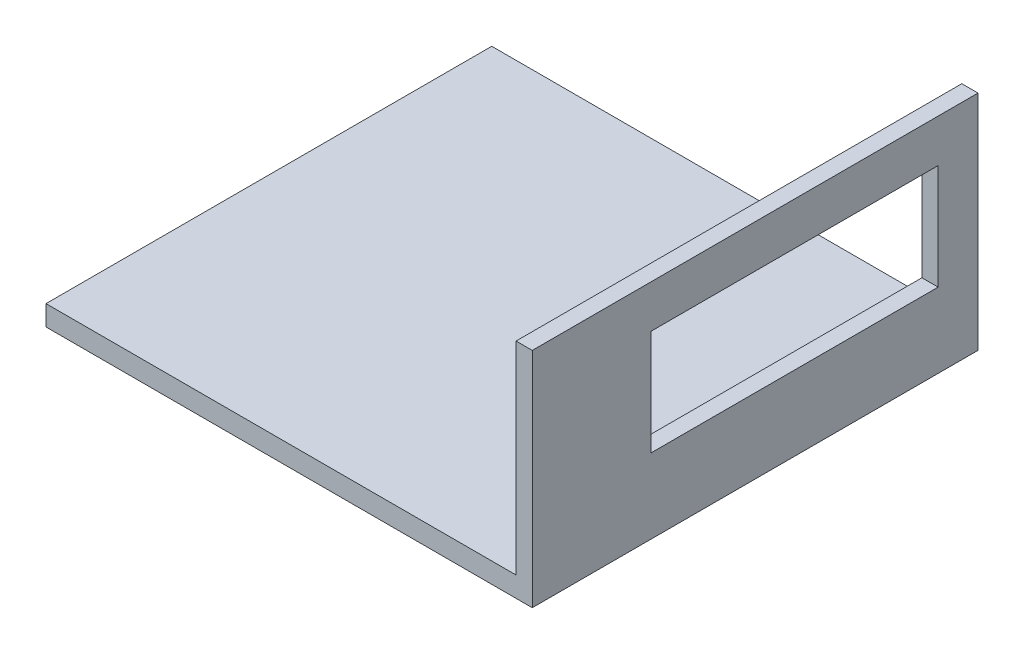
SolidWorks part; units mm, degrees
ref_plane "Front Plane" through (0, 0, 0) normal (0, 0, 1) x (1, 0, 0)
ref_plane "Top Plane" through (0, 0, 0) normal (0, 1, 0) x (1, 0, 0)
ref_plane "Right Plane" through (0, 0, 0) normal (1, 0, 0) x (0, 0, -1)
sketch "Sketch1" plane through (0, 0, 0) normal (0, 1, 0) x (1, 0, 0)
  line L1 (-60, -55) -> (60, -55)
  line L2 (-60, -55) -> (-60, 55)
  line L3 (-60, 55) -> (60, 55)
  line L4 (60, -55) -> (60, 55)
  line L5 (-60, -55) -> (60, 55) construction
  line L6 (-60, 55) -> (60, -55) construction
  point P0 (0, 0)
  dimension "D1" = 120
  dimension "D2" = 110
extrude "Boss-Extrude1" add sketch "Sketch1" along normal blind 5
sketch "Sketch2" plane through (0, 5, 0) normal (0, 1, 0) x (1, 0, 0)
  line L0 (60, -55) -> (60, 55)
  line L1 (60, -55) -> (56, -55)
  line L2 (60, 55) -> (56, 55)
  line L3 (56, -55) -> (56, 55)
  dimension "D1" = 4
extrude "Boss-Extrude2" add sketch "Sketch2" along normal blind 50
sketch "Sketch3" plane through (60, 0, 0) normal (1, 0, 0) x (0, 0, -1)
  line L1 (-25.7586, 18.4415) -> (45.1615, 18.4415)
  line L2 (-25.7586, 18.4415) -> (-25.7586, 44.4295)
  line L3 (-25.7586, 44.4295) -> (45.1615, 44.4295)
  line L4 (45.1615, 18.4415) -> (45.1615, 44.4295)
extrude "Cut-Extrude1" cut sketch "Sketch3" against normal up to next
